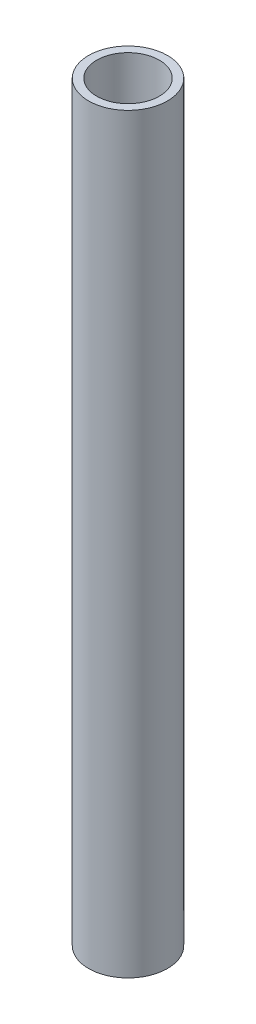
SolidWorks part; units mm, degrees
ref_plane "Front Plane" through (0, 0, 0) normal (0, 0, 1) x (1, 0, 0)
ref_plane "Top Plane" through (0, 0, 0) normal (0, 1, 0) x (1, 0, 0)
ref_plane "Right Plane" through (0, 0, 0) normal (1, 0, 0) x (0, 0, -1)
sketch "Sketch1" plane through (0, 0, 0) normal (0, 1, 0) x (1, 0, 0)
  circle A0 centre (0, 0) radius 8.001
  circle A1 centre (0, 0) radius 6.35
  dimension "D1" = 16.002
  dimension "D2" = 12.7
extrude "Boss-Extrude1" add sketch "Sketch1" along normal blind 152.4
